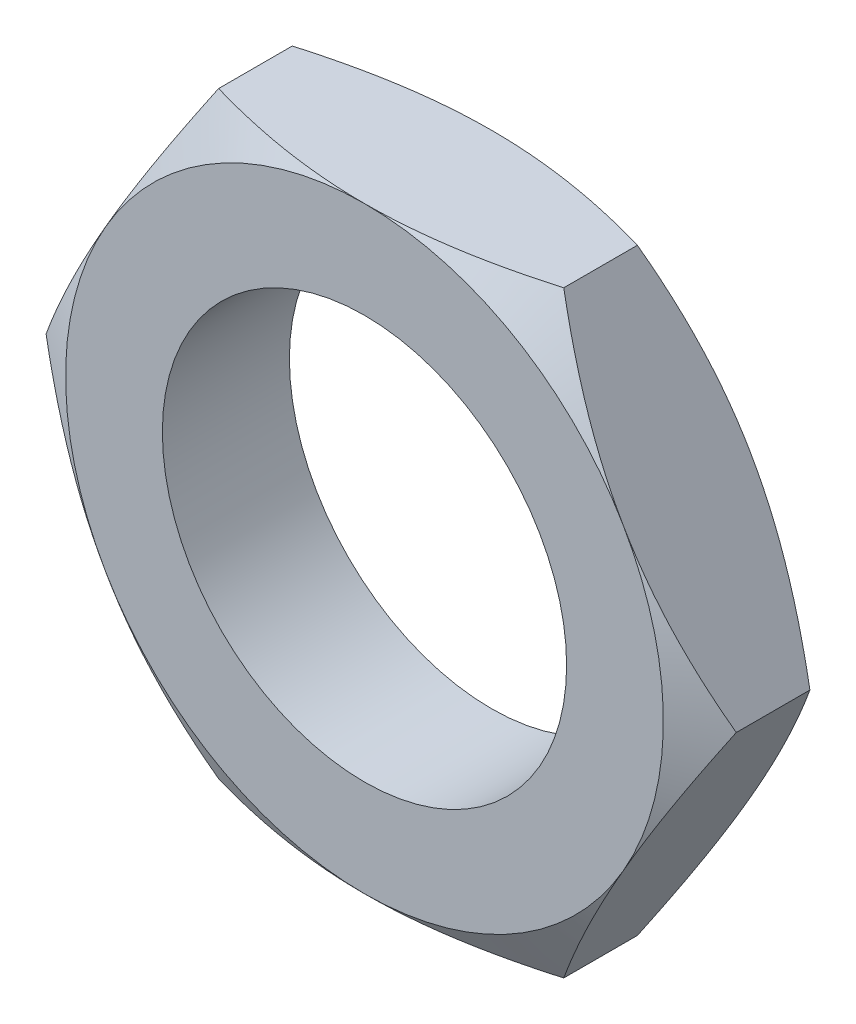
SolidWorks part; units mm, degrees
ref_plane "Front Plane" through (0, 0, 0) normal (0, 0, 1) x (1, 0, 0)
ref_plane "Top Plane" through (0, 0, 0) normal (0, 1, 0) x (1, 0, 0)
ref_plane "Right Plane" through (0, 0, 0) normal (1, 0, 0) x (0, 0, -1)
sketch "Sketch1" plane through (0, 0, 0) normal (0, 0, 1) x (1, 0, 0)
  line L1 (2.3094, 4) -> (-2.3094, 4)
  line L2 (-2.3094, 4) -> (-4.6188, 0)
  line L3 (-4.6188, 0) -> (-2.3094, -4)
  line L4 (-2.3094, -4) -> (2.3094, -4)
  line L5 (2.3094, -4) -> (4.6188, 0)
  line L6 (4.6188, 0) -> (2.3094, 4)
  circle A0 centre (0, 0) radius 4
  dimension "D1" = 8
extrude "Boss-Extrude1" add sketch "Sketch1" along normal mid plane 1.7 contours L3 L4 L5 L6 L1 L2
sketch "Sketch2" plane through (0, 0, 0.85) normal (0, 0, 1) x (1, 0, 0)
  circle A0 centre (0, 0) radius 4 construction
  circle A1 centre (0, 0) radius 4
extrude "Cut-Extrude-Thin2" cut sketch "Sketch2" against normal blind 1 draft 60 flip side to cut thin
mirror "Mirror1" about plane through (0, 0, 0) normal (0, 0, 1) of "Cut-Extrude-Thin2"
hole_wizard "1/4-28 Tapped Hole1" positions "Sketch3" profile "Sketch4" tap size "1/4-28" standard "ANSI Inch" end condition through all
sketch "Sketch3" plane through (0, 0, 0.85) normal (0, 0, 1) x (1, 0, 0)
  point P0 (0, 0)
cosmetic thread "Hole Thread1" parameters "D2"=6.35
sketch "Sketch4" plane through (0, 0, 0.85) normal (1, 0, 0) x (0, -1, 0)
  line L0 (0, 0) -> (0, 1.7)
  line L1 (0, 1.7) -> (2.7051, 1.7)
  line L2 (2.7051, 1.7) -> (2.7051, 0)
  line L5 (2.7051, 0) -> (0, 0)
  line L11 (0, -6.35) -> (0, 107.95) construction
  dimension "Thru Tap Drill Dia." = 5.4102
  dimension "Thru Tap Drill Depth" = 1.7
